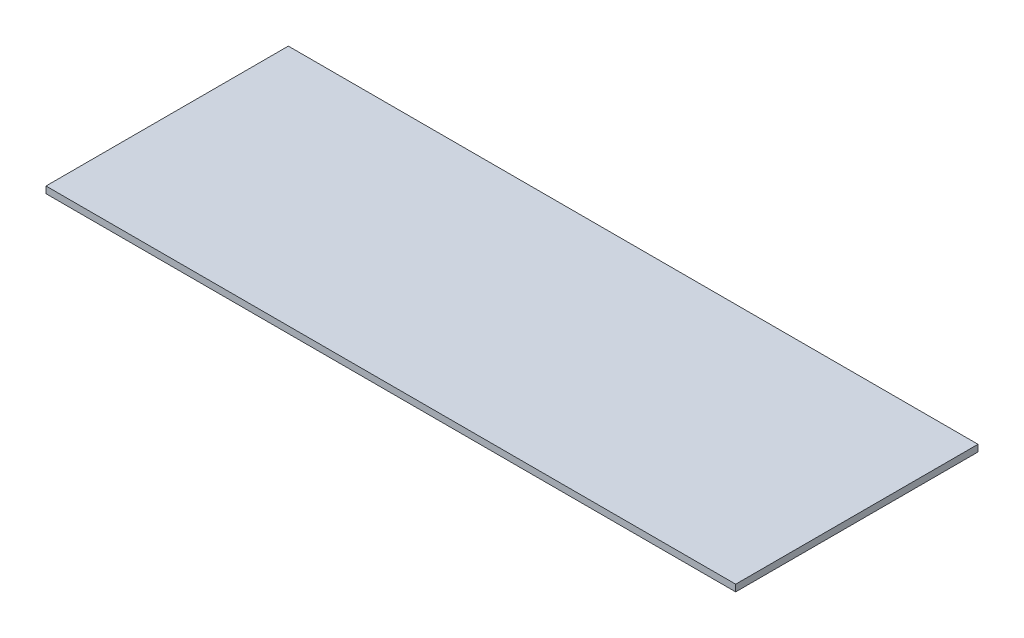
SolidWorks part; units mm, degrees
ref_plane "Ebene vorne" through (0, 0, 0) normal (0, 0, 1) x (1, 0, 0)
ref_plane "Ebene oben" through (0, 0, 0) normal (0, 1, 0) x (1, 0, 0)
ref_plane "Ebene rechts" through (0, 0, 0) normal (1, 0, 0) x (0, 0, -1)
sketch "Skizze1" plane through (0, 0, 0) normal (0, 1, 0) x (1, 0, 0)
  line L1 (0, 0) -> (1850, 0)
  line L2 (0, 0) -> (0, 650)
  line L3 (0, 650) -> (1850, 650)
  line L4 (1850, 0) -> (1850, 650)
  dimension "D1" = 1850
  dimension "D2" = 650
extrude "Aufsatz-Linear austragen1" add sketch "Skizze1" along normal blind 18
